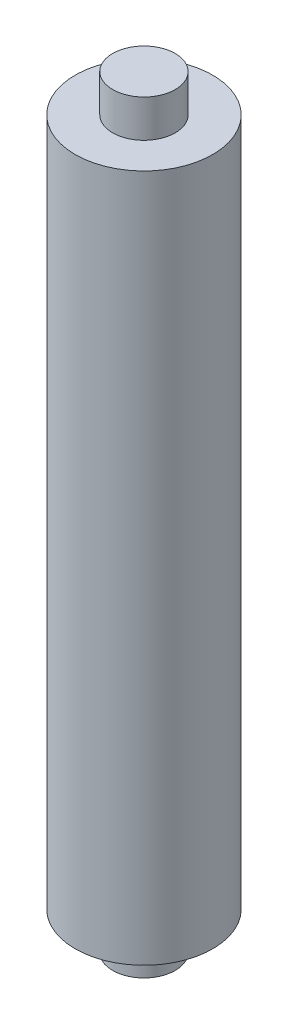
SolidWorks part; units mm, degrees
ref_plane "前视基准面" through (0, 0, 0) normal (0, 0, 1) x (1, 0, 0)
ref_plane "上视基准面" through (0, 0, 0) normal (0, 1, 0) x (1, 0, 0)
ref_plane "右视基准面" through (0, 0, 0) normal (1, 0, 0) x (0, 0, -1)
other "Configuration Table"
sketch "草图1" plane through (0, 0, 0) normal (0, 1, 0) x (1, 0, 0)
  circle A0 centre (0, 0) radius 2.5
  dimension "D1" = 5
extrude "凸台-拉伸1" add sketch "草图1" along normal mid plane 61
sketch "草图2" plane through (0, 0, 0) normal (0, 1, 0) x (1, 0, 0)
  circle A0 centre (0, 0) radius 5.5
  dimension "D1" = 11
extrude "凸台-拉伸2" add sketch "草图2" along normal mid plane 55
